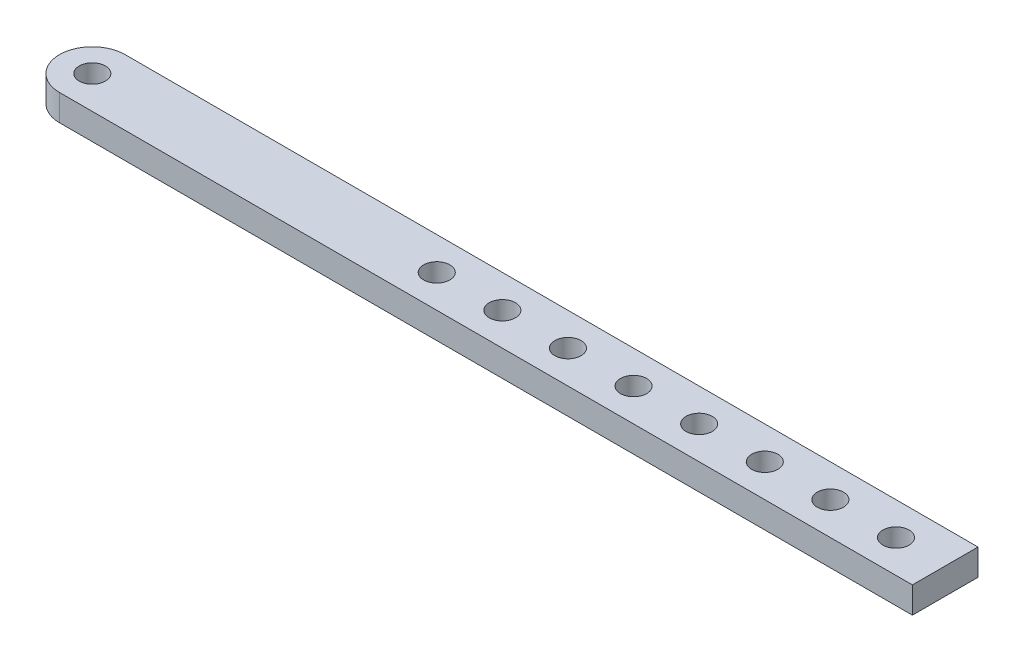
SolidWorks part; units mm, degrees
ref_plane "Front Plane" through (0, 0, 0) normal (0, 0, 1) x (1, 0, 0)
ref_plane "Top Plane" through (0, 0, 0) normal (0, 1, 0) x (1, 0, 0)
ref_plane "Right Plane" through (0, 0, 0) normal (1, 0, 0) x (0, 0, -1)
sketch "Sketch1" plane through (0, 0, 0) normal (0, 1, 0) x (1, 0, 0)
  line L0 (0, -10) -> (0, 10) construction
  line L2 (0, 10) -> (260, 10)
  line L4 (0, -10) -> (260, -10)
  line L5 (260, 10) -> (260, -10)
  arc A0 (0, 10) -> (0, -10) centre (0, 0) ccw
  dimension "D2" = 10
  dimension "D1" = 20
  dimension "D3" = 260
extrude "Boss-Extrude1" add sketch "Sketch1" along normal blind 8
sketch "Sketch2" plane through (0, 8, 0) normal (0, 1, 0) x (1, 0, 0)
  circle A0 centre (0, 0) radius 4
  dimension "D1" = 8
extrude "Cut-Extrude1" cut sketch "Sketch2" against normal blind 8
sketch "Sketch3" plane through (0, 8, 0) normal (0, 1, 0) x (1, 0, 0)
  line L0 (260, -10) -> (260, 10) construction
  line L1 (260, 10) -> (0, 10) construction
  circle A0 centre (245, 0) radius 4
  dimension "D1" = 8
  dimension "D2" = 15
  dimension "D3" = 10
extrude "Cut-Extrude2" cut sketch "Sketch3" against normal blind 10
pattern_linear "LPattern1" count 8 spacing 20 along (-1, 0, 0) of "Cut-Extrude2"
